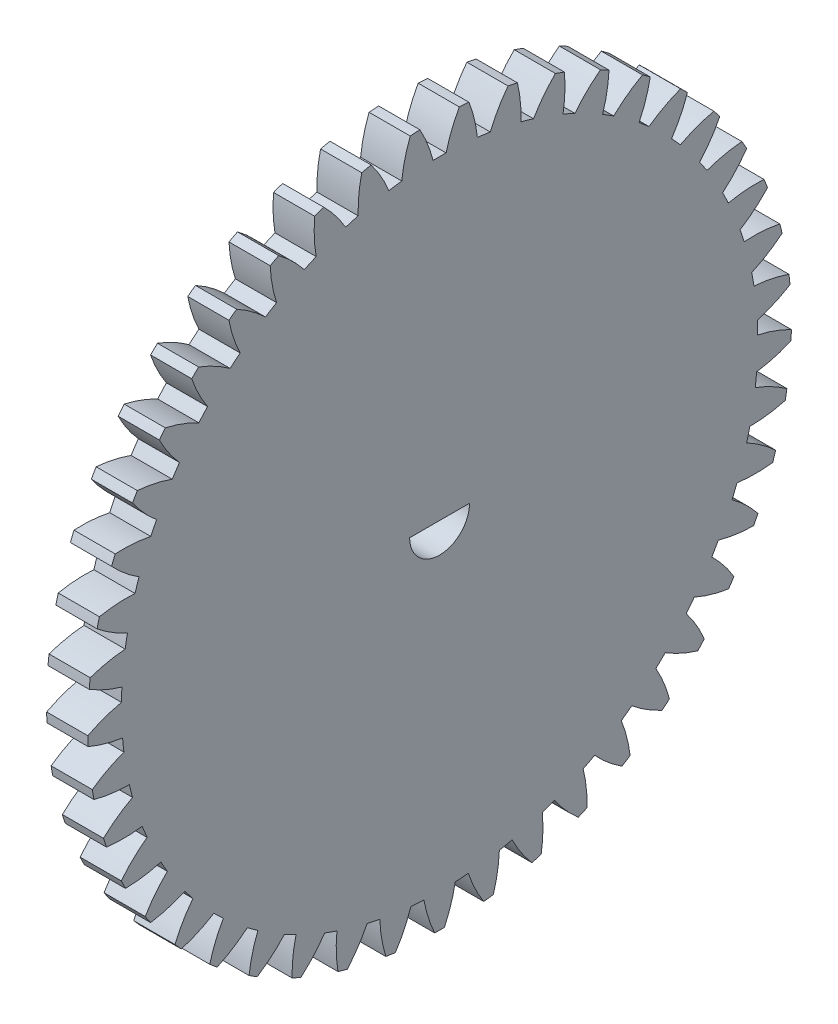
SolidWorks part; units mm, degrees
ref_plane "Plane1" through (0, 0, 0) normal (0, 0, 1) x (1, 0, 0)
ref_plane "Plane2" through (0, 0, 0) normal (0, 1, 0) x (1, 0, 0)
ref_plane "Plane3" through (0, 0, 0) normal (1, 0, 0) x (0, 0, -1)
sketch "HoldingSke" plane through (0, 0, 0) normal (0, 1, 0) x (1, 0, 0)
  line L0 (0, 0) -> (0.3536, -0.3536)
  line L1 (-15, 0) -> (100, 0) construction
  line L2 (0, 0) -> (-2.1039, 2.3779)
  line L3 (0, 0) -> (-11.863, 4.5341)
  line L4 (0, 0) -> (6.1066, 6.1066)
  line L5 (0, 0) -> (-46.8476, -17.4728)
  line L6 (0, 0) -> (-4.5593, -3.0762)
  line L7 (-2.1039, 2.3779) -> (8.6586, 51.2059)
  line L8 (-76.2, 54.61) -> (-76.1, 54.61)
  line L9 (-71.009, 38.7566) -> (-53.1078, 45.2721)
  line L10 (-76.2, 71.12) -> (104.1128, 71.12)
  line L11 (0, 0) -> (-5.5, 0)
  line L12 (-76.2, 101.6) -> (-76.133, 101.6)
  line L13 (24.9733, 27.94) -> (52.9518, 28.4284)
  line L14 (24.9733, 27.94) -> (24.9743, 27.94)
  line L15 (24.9733, 27.94) -> (100.4006, 29.5858)
  line L16 (-63.627, -2) -> (-12.827, -2)
  circle A0 centre (0, 0) radius 0.4
  circle A1 centre (0, 0) radius 37.5
  circle A2 centre (0, 0) radius 37.5
  circle A3 centre (0, 0) radius 0.4
  dimension "MHD" = 75
  dimension "Hub_dia" = 75
  dimension "Bore" = 0.8
  dimension "MBD" = 0.8
  dimension "Num_teeth" = 45
  dimension "Pitch" = 0.5
  dimension "Overall_len" = 50
  dimension "Show_teeth" = 45
  dimension "Thickness" = 5.5
  dimension "OAL" = 50.0001
  dimension "T_dim" = 0.1
  dimension "Ap" = 20
  dimension "H" = 19.05
  dimension "Pitch_radius" = 180.3128
  dimension "Width" = 5.5
  dimension "Backlash" = 0.067
  dimension "Addendum_fac" = 1
  dimension "Dedendum_fac" = 1.25
  dimension "Clearance_fac" = 0.25
  dimension "Dedendum_add" = 0.001
  dimension "Module" = 2
sketch "BasProSke" plane through (0, 0, 0) normal (0, 1, 0) x (1, 0, 0)
  line L0 (-10, 0) -> (60, 0) construction
  line L1 (0, 0) -> (0, 47)
  line L2 (0, 0) -> (5.5, 0)
  line L3 (5.5, 0) -> (5.5, 47)
  line L4 (5.5, 47) -> (0, 47)
  dimension "Thickness" = 5.5
  dimension "Diameter" = 94
revolve "Base-Revolve" add sketch "BasProSke" angle 360 about L0
sketch "TooCutSke" plane through (0, 0, 0) normal (1, 0, 0) x (0, 0, -1)
  line L1 (0, 0) -> (0, 107) construction
  line L2 (0, 0) -> (-1.6877, 44.9683) construction
  line L3 (0, 0) -> (-6.2748, 89.7339) construction
  line L4 (-1.6877, 44.9683) -> (-3.1374, 44.867) construction
  arc A0 (0.8706, 42.4901) -> (-0.8706, 42.4901) centre (0, 0) ccw
  arc A1 (2.6509, 46.9506) -> (-2.6509, 46.9506) centre (0, 0) ccw
  circle A2 centre (0, 0) radius 45 construction
  circle A3 centre (0, 0) radius 42.2862 construction
  arc A4 (-0.8706, 42.4901) -> (-2.6509, 46.9506) centre (-18.3289, 38.1074) ccw
  arc A5 (2.6509, 46.9506) -> (0.8706, 42.4901) centre (18.3289, 38.1074) ccw
  dimension "Root_dia" = 84.998
  dimension "Overcut_dia" = 94.0508
  dimension "Pitch_dia" = 90
  dimension "Base_dia" = 84.5723
  dimension "Flank_rad" = 18
  dimension "Half_ang" = 4
  dimension "Half_CT" = 1.4532
extrude "ToothCut" cut sketch "TooCutSke" along normal through all
fillet "Breaks" [suppressed] radius 0.04
fillet "RootFillets" [suppressed] radius 0.501
pattern_circular "TeethCuts" count 45 every 8 about axis through (-10, 0, 0) along (1, 0, 0) of "ToothCut", "RootFillets", "Breaks"
sketch "HubNeaOneSke" plane through (0, 0, 0) normal (-1, 0, 0) x (0, 0, 1)
  circle A0 centre (0, 0) radius 37.5
  dimension "Diameter" = 75
extrude "HubNearOne" [suppressed] add sketch "HubNeaOneSke" along normal blind 44.5001
sketch "HubNeaBotSke" plane through (0, 0, 0) normal (-1, 0, 0) x (0, 0, 1)
  circle A0 centre (0, 0) radius 37.5
  dimension "Diameter" = 75
extrude "HubNearBoth" [suppressed] add sketch "HubNeaBotSke" along normal blind 22.25
ref_plane "FarPln" through (5.5, 0, 0) normal (1, 0, 0) x (0, 0, -1)
sketch "HubFarSke" plane through (5.5, 0, 0) normal (1, 0, 0) x (0, 0, -1)
  circle A0 centre (0, 0) radius 37.5
  dimension "Diameter" = 75
extrude "HubFar" [suppressed] add sketch "HubFarSke" along normal blind 22.25
sketch "BorSke" plane through (0, 0, 0) normal (1, 0, 0) x (0, 0, -1)
  circle A0 centre (0, 0) radius 0.4
  dimension "Diameter" = 0.8
extrude "Bore" cut sketch "BorSke" along normal mid plane 100.0001
sketch "KeySke" plane through (0, 0, 0) normal (1, 0, 0) x (0, 0, -1)
  line L0 (-0.05, 0) -> (-0.05, 0.5)
  line L1 (-0.05, 0.5) -> (0.05, 0.5)
  line L2 (0.05, 0.5) -> (0.05, 0)
  line L3 (0, 0) -> (0, 34) construction
  line L4 (-0.05, 0) -> (0.05, 0)
  dimension "Offset" = 0.5
  dimension "Width" = 0.1
extrude "Keyway" [suppressed] cut sketch "KeySke" along normal mid plane 100.0001
pattern_circular "Keyway2" [suppressed] count 2 every 90 about axis through (-10, 0, 0) along (1, 0, 0)
sketch "Croquis1" plane through (5.5, 0, 0) normal (1, 0, 0) x (0, 0, -1)
  line L0 (-4, 0.4) -> (4, 0.4)
  arc A0 (-4, 0.4) -> (4, 0.4) centre (0, 0.4) ccw
  circle A1 centre (0, 0) radius 0.4 construction
  dimension "D1" = 8
extrude "Cortar-Extruir1" cut sketch "Croquis1" against normal blind 6
equation "' \"Module@HoldingSke\" = 6.35"
equation "' \"Num_teeth@HoldingSke\" = 12"
equation "' \"Ap@HoldingSke\" =  20"
equation "' \"Ap@HoldingSke\" = 20"
equation "' \"Width@HoldingSke\" = 0.5 * 25.4"
equation "' \"Hub_dia@HoldingSke\"= 1 * 25.4"
equation "' \"Hub_dia@HoldingSke\" = 1 * 25.4"
equation "' \"Overall_len@HoldingSke\" = 1.0 * 25.4"
equation "' \"Bore@HoldingSke\" = 0.75 * 25.4"
equation "' \"T_dim@HoldingSke\" = 0.1 * 25.4"
equation "' \"Width@KeySke\" = 0.25 * 25.4"
equation "' \"Show_teeth@HoldingSke\" = 13"
equation "' \"Backlash@HoldingSke\" = 0.009 * 25.4"
equation "' \"Addendum_fac@HoldingSke\" = 1.0"
equation "' \"Dedendum_fac@HoldingSke\" = 1.25"
equation "' \"Dedendum_add@HoldingSke\" = 0.00005 * 25.4"
equation "' \"Clearance_fac@HoldingSke\" = 0.25"
equation "\"Pitch@HoldingSke\" = 1 / \"Module@HoldingSke\""
equation "\"Overcut_dia@TooCutSke\" = (\"Num_teeth@HoldingSke\" + 2 * \"Addendum_fac@HoldingSke\") / \"Pitch@HoldingSke\" + 0.002 * 25.4"
equation "\"Pitch_dia@TooCutSke\" = \"Num_teeth@HoldingSke\" / \"Pitch@HoldingSke\""
equation "\"Base_dia@TooCutSke\" = \"Num_teeth@HoldingSke\" / \"Pitch@HoldingSke\" * cos((\"Ap@HoldingSke\"  * 3.14159265 / 180))"
equation "\"Root_dia@TooCutSke\" = (\"Num_teeth@HoldingSke\" + 2) / \"Pitch@HoldingSke\" - 2 * (\"Addendum_fac@HoldingSke\" + \"Dedendum_fac@HoldingSke\") / \"Pitch@HoldingSke\" - \"Dedendum_add@HoldingSke\" * 2"
equation "\"Half_ang@TooCutSke\" = 180 / \"Num_teeth@HoldingSke\""
equation "\"Half_CT@TooCutSke\" = \"Num_teeth@HoldingSke\" / \"Pitch@HoldingSke\" * sin((3.14159265 / 2 / \"Num_teeth@HoldingSke\")) / 2 - 7 * \"Backlash@HoldingSke\" / 4"
equation "\"Flank_rad@TooCutSke\" = \"Num_teeth@HoldingSke\" / \"Pitch@HoldingSke\" / 5"
equation "\"Radius@RootFillets\" = \"Clearance_fac@HoldingSke\" / \"Pitch@HoldingSke\" + \"Dedendum_add@HoldingSke\""
equation "\"Break_rad@Breaks\" = 0.02 / \"Pitch@HoldingSke\""
equation "\"Thickness@HoldingSke\" = \"Width@HoldingSke\""
equation "\"OAL@HoldingSke\" = \"Thickness@HoldingSke\""
equation "\"MHD@HoldingSke\" = (\"Num_teeth@HoldingSke\" + 2) / \"Pitch@HoldingSke\" - 2 * (\"Addendum_fac@HoldingSke\" + \"Dedendum_fac@HoldingSke\")  / \"Pitch@HoldingSke\" - \"Dedendum_add@HoldingSke\" * 2"
equation "\"MBD@HoldingSke\" = (\"Num_teeth@HoldingSke\" + 2) / \"Pitch@HoldingSke\" - 2 * (\"Addendum_fac@HoldingSke\" + \"Dedendum_fac@HoldingSke\")  / \"Pitch@HoldingSke\" - \"Dedendum_add@HoldingSke\" * 2 - 0.002 * 25.4"
equation "\"MHD@HoldingSke\" = ((sgn( \"MHD@HoldingSke\" - \"Hub_dia@HoldingSke\" )-1)*( \"MHD@HoldingSke\" - \"Hub_dia@HoldingSke\" ))/-2+ \"Hub_dia@HoldingSke\""
equation "\"MBD@HoldingSke\" = ((sgn( \"MBD@HoldingSke\" - \"Bore@HoldingSke\" )-1)*( \"MBD@HoldingSke\" - \"Bore@HoldingSke\" ))/-2+ \"Bore@HoldingSke\""
equation "\"OAL@HoldingSke\" = ((sgn( \"OAL@HoldingSke\" - \"Overall_len@HoldingSke\" )+1)*( \"OAL@HoldingSke\" - \"Overall_len@HoldingSke\" ))/2 + \"Overall_len@HoldingSke\" + 0.000002 * 25.4"
equation "\"Num_teeth@TeethCuts\" = int( \"Show_teeth@HoldingSke\" ) + 1"
equation "\"Num_teeth@TeethCuts\" = ((sgn( \"Num_teeth@TeethCuts\" - \"Num_teeth@HoldingSke\" )-1)*( \"Num_teeth@TeethCuts\" - \"Num_teeth@HoldingSke\" ))/-2+ \"Num_teeth@HoldingSke\""
equation "\"Num_teeth@TeethCuts\" = ((sgn( \"Num_teeth@TeethCuts\" - 2.0)+1)*( \"Num_teeth@TeethCuts\" - 2.0))/2 +2.0"
equation "\"Angle@TeethCuts\" = 360.0 / \"Num_teeth@HoldingSke\""
equation "\"Diameter@BasProSke\" = (\"Num_teeth@HoldingSke\" + 2 * \"Addendum_fac@HoldingSke\") / \"Pitch@HoldingSke\""
equation "\"Thickness@BasProSke\"  = \"Thickness@HoldingSke\""
equation "' \"Fillet_rad@BasProSke\" =  \"Thickness@HoldingSke\" * 0.05"
equation "' \"Fillet_rad@BasProSke\" = \"Thickness@HoldingSke\" * 0.05"
equation "\"MHD@HoldingSke\" = ((sgn( \"MHD@HoldingSke\" - \"Root_dia@TooCutSke\" )-1)*( \"MHD@HoldingSke\" - \"Root_dia@TooCutSke\" ))/-2+ \"Root_dia@TooCutSke\""
equation "\"Diameter@HubNeaOneSke\" = \"MHD@HoldingSke\""
equation "\"Length@HubNearOne\" = \"OAL@HoldingSke\" - \"Thickness@BasProSke\""
equation "\"Diameter@HubNeaBotSke\" = \"MHD@HoldingSke\""
equation "\"Length@HubNearBoth\" = ( \"OAL@HoldingSke\" - \"Thickness@BasProSke\" ) / 2.0"
equation "\"Thickness@FarPln\" = \"Thickness@BasProSke\""
equation "\"Diameter@HubFarSke\" = \"MHD@HoldingSke\""
equation "\"Length@HubFar\" = ( \"OAL@HoldingSke\" - \"Thickness@BasProSke\" ) / 2.0"
equation "\"Diameter@BorSke\" = \"MBD@HoldingSke\""
equation "\"D1@Bore\" = \"OAL@HoldingSke\" * 2.0"
equation "\"D1@Keyway\" = \"OAL@HoldingSke\" * 2.0"
equation "\"Offset@KeySke\" = \"T_dim@HoldingSke\" + \"MBD@HoldingSke\" / 2.0"
